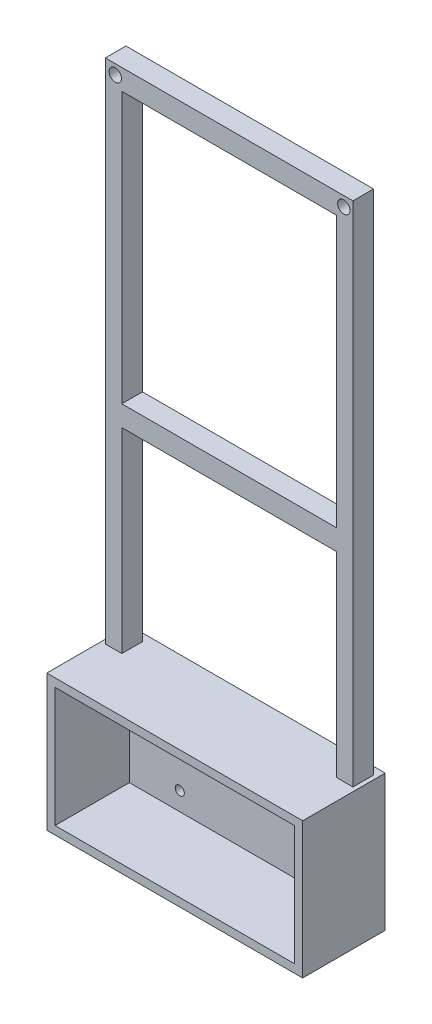
SolidWorks part; units mm, degrees
ref_plane "Front Plane" through (0, 0, 0) normal (0, 0, 1) x (1, 0, 0)
ref_plane "Top Plane" through (0, 0, 0) normal (0, 1, 0) x (1, 0, 0)
ref_plane "Right Plane" through (0, 0, 0) normal (1, 0, 0) x (0, 0, -1)
sketch "Sketch1" plane through (0, 0, 0) normal (0, 0, 1) x (1, 0, 0)
  line L1 (-31, -16.5) -> (31, -16.5)
  line L2 (-31, -16.5) -> (-31, 16.5)
  line L3 (-31, 16.5) -> (31, 16.5)
  line L4 (31, -16.5) -> (31, 16.5)
  line L5 (-31, -16.5) -> (31, 16.5) construction
  line L6 (-31, 16.5) -> (31, -16.5) construction
  point P0 (0, 0)
  dimension "D1" = 62
  dimension "D2" = 33
extrude "Boss-Extrude1" add sketch "Sketch1" along normal blind 20
shell "Shell1" thickness 2
sketch "Sketch2" plane through (0, 16.5, 0) normal (0, 1, 0) x (1, 0, 0)
  line L0 (-28, -4.3245) -> (28, -4.3245) construction
  line L2 (-30, -6.8245) -> (-26, -6.8245)
  line L3 (-30, -6.8245) -> (-30, -1.8245)
  line L4 (-30, -1.8245) -> (-26, -1.8245)
  line L5 (-26, -6.8245) -> (-26, -1.8245)
  line L6 (-30, -6.8245) -> (-26, -1.8245) construction
  line L7 (-30, -1.8245) -> (-26, -6.8245) construction
  line L8 (26, -6.8245) -> (30, -6.8245)
  line L9 (26, -6.8245) -> (26, -1.8245)
  line L10 (26, -1.8245) -> (30, -1.8245)
  line L11 (30, -6.8245) -> (30, -1.8245)
  line L12 (26, -6.8245) -> (30, -1.8245) construction
  line L13 (26, -1.8245) -> (30, -6.8245) construction
  point P3 (0, -4.3245)
  dimension "D1" = 5
  dimension "D2" = 4
  dimension "D3" = 5
  dimension "D4" = 4
extrude "Boss-Extrude2" add sketch "Sketch2" along normal blind 123
sketch "Sketch3" plane through (-26, 0, 0) normal (1, 0, 0) x (0, 0, -1)
  line L0 (-4.3245, 16.5) -> (-4.3245, 66.4173)
  line L1 (-6.8245, 16.5) -> (-1.8245, 16.5) construction
  line L2 (-1.8245, 139.5) -> (-1.8245, 16.5) construction
  line L3 (-6.8245, 63.9173) -> (-1.8245, 63.9173)
  line L4 (-6.8245, 63.9173) -> (-6.8245, 68.9173)
  line L5 (-6.8245, 68.9173) -> (-1.8245, 68.9173)
  line L6 (-1.8245, 63.9173) -> (-1.8245, 68.9173)
  line L7 (-6.8245, 63.9173) -> (-1.8245, 68.9173) construction
  line L8 (-6.8245, 68.9173) -> (-1.8245, 63.9173) construction
  dimension "D1" = 5
extrude "Boss-Extrude3" add sketch "Sketch3" along normal blind 53 contours L5 L6 L3 L4
sketch "Sketch4" plane through (-26, 0, 0) normal (1, 0, 0) x (0, 0, -1)
  line L0 (-1.8245, 139.5) -> (-1.8245, 16.5) construction
  line L1 (-6.8245, 139.5) -> (-1.8245, 139.5)
  line L2 (-6.8245, 139.5) -> (-6.8245, 134.5002)
  line L3 (-6.8245, 134.5002) -> (-1.8245, 134.5002)
  line L4 (-1.8245, 139.5) -> (-1.8245, 134.5002)
  line L5 (-6.8245, 139.5) -> (-1.8245, 134.5002) construction
  line L6 (-6.8245, 134.5002) -> (-1.8245, 139.5) construction
  point P4 (-4.3245, 137.0001)
extrude "Boss-Extrude4" add sketch "Sketch4" along normal blind 53
sketch "Sketch5" plane through (0, 0, 6.8245) normal (0, 0, 1) x (1, 0, 0)
  circle A0 centre (-27.5882, 137.1224) radius 1.5
  circle A1 centre (27.8023, 137.1224) radius 1.5
extrude "Cut-Extrude1" cut sketch "Sketch5" against normal blind 53
sketch "Sketch6" plane through (0, 0, 0) normal (0, 0, -1) x (-1, 0, 0)
  circle A0 centre (-18.2184, 9.9593) radius 1.1
  circle A1 centre (-18.2184, -10.0407) radius 1.1
  circle A2 centre (16.7816, -10.0407) radius 1.1
  circle A3 centre (16.7816, 9.9593) radius 1.1
  point P8 (0, 0)
extrude "Cut-Extrude2" cut sketch "Sketch6" against normal blind 10
